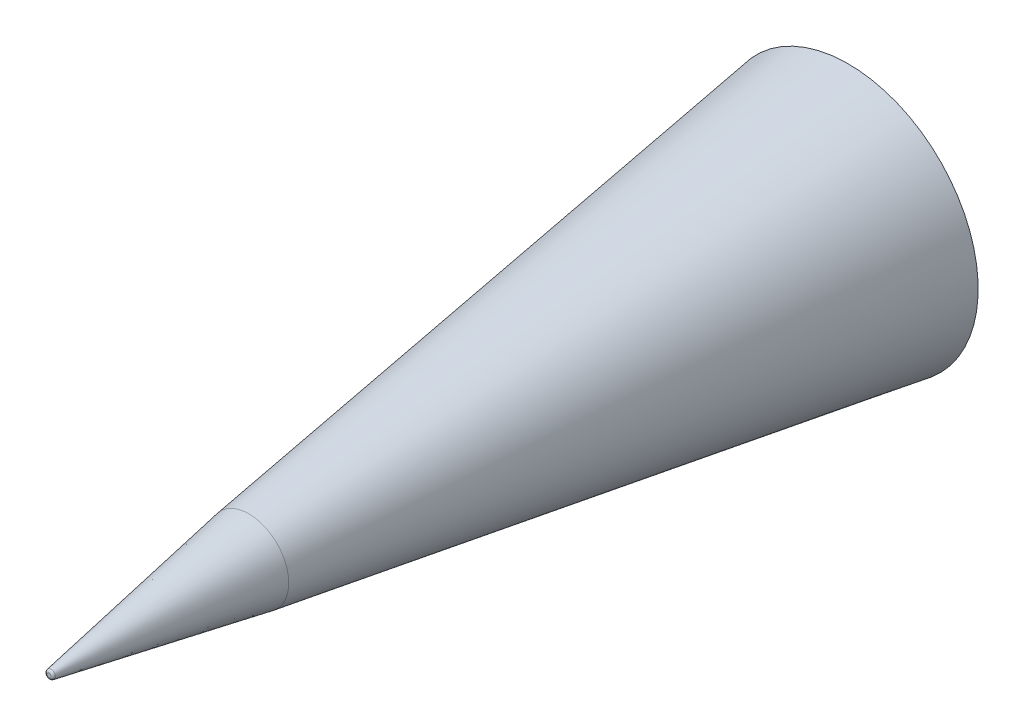
SolidWorks part; units mm, degrees
ref_plane "Спереди" through (0, 0, 0) normal (0, 0, 1) x (1, 0, 0)
ref_plane "Сверху" through (0, 0, 0) normal (0, 1, 0) x (1, 0, 0)
ref_plane "Справа" through (0, 0, 0) normal (1, 0, 0) x (0, 0, -1)
sketch "Эскиз1" plane through (0, 0, 0) normal (1, 0, 0) x (0, 0, -1)
  line L0 (-107.5728, 0) -> (109.2252, 0) construction
  line L1 (5, 1) -> (0, 0.1)
  line L2 (0, 0.1) -> (0, 0)
  line L3 (5, 1) -> (20, 3.25)
  line L4 (20, 0) -> (0, 0)
  line L5 (20, 3.25) -> (20, 0)
  dimension "D1" = 0.1
  dimension "D2" = 3.25
  dimension "D3" = 1
  dimension "D4" = 5
  dimension "D5" = 15
revolve "Повернуть1" add sketch "Эскиз1" angle 360 about L0
fillet "Скругление3" radius 0.06 1 edges at (0.1, 0, 0)
sketch "Эскиз3" plane through (0, 0, -20) normal (0, 0, -1) x (-1, 0, 0)
  line L1 (3.2588, -1.8554) -> (3.2362, 1.8945)
  line L2 (3.2362, 1.8945) -> (-0.0226, 3.7499)
  line L3 (-0.0226, 3.7499) -> (-3.2588, 1.8554)
  line L4 (-3.2588, 1.8554) -> (-3.2362, -1.8945)
  line L5 (-3.2362, -1.8945) -> (0.0226, -3.7499)
  line L6 (0.0226, -3.7499) -> (3.2588, -1.8554)
  circle A0 centre (0, 0) radius 3.75 construction
